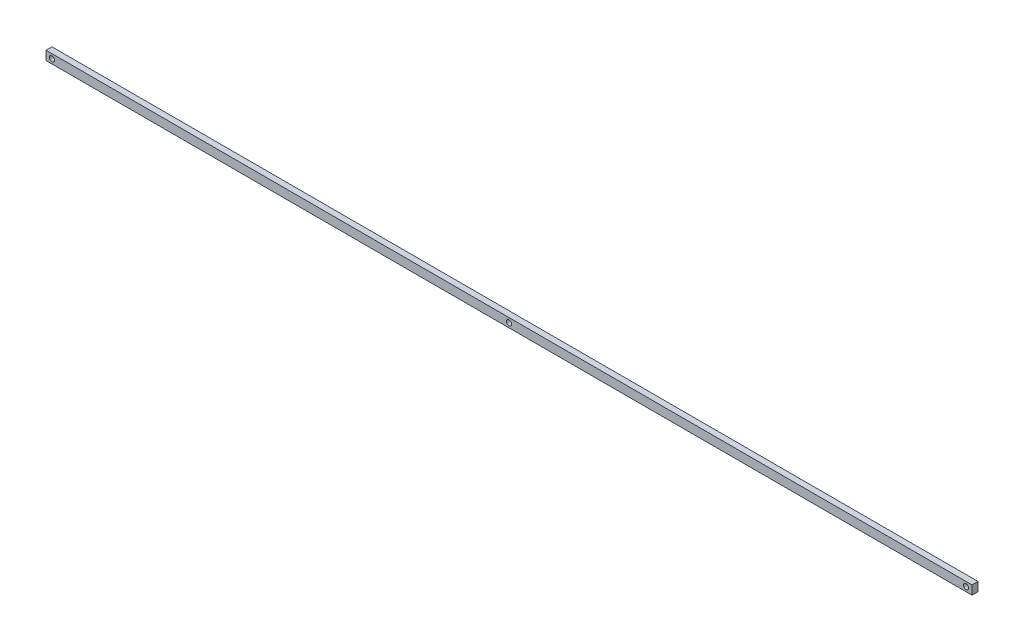
SolidWorks part; units mm, degrees
material "ASTM A36 Steel"
ref_plane "Front Plane" through (0, 0, 0) normal (0, 0, 1) x (1, 0, 0)
ref_plane "Top Plane" through (0, 0, 0) normal (0, 1, 0) x (1, 0, 0)
ref_plane "Right Plane" through (0, 0, 0) normal (1, 0, 0) x (0, 0, -1)
sketch "Sketch1" plane through (0, 0, 0) normal (0, 0, 1) x (1, 0, 0)
  line L0 (55, 0) -> (-55, 0) construction
  line L1 (0, 0) -> (1556, 0)
  line L2 (0, 0) -> (0, 15)
  line L3 (0, 15) -> (1556, 15)
  line L4 (1556, 0) -> (1556, 15)
  dimension "D1" = 1556
  dimension "D2" = 15
extrude "Boss-Extrude1" add sketch "Sketch1" along normal blind 10
sketch "Sketch2" plane through (0, 0, 10) normal (0, 0, 1) x (1, 0, 0)
  line L0 (0, 15) -> (0, 0) construction
  line L1 (0, 7.5) -> (-51.7723, 7.5) construction
  line L2 (778, 15) -> (778, 145.9267) construction
  line L3 (1556, 0) -> (1556, 15) construction
  line L4 (1556, 15) -> (0, 15) construction
  circle A0 centre (10, 7.5) radius 4.255
  circle A1 centre (1546, 7.5) radius 4.255
  circle A2 centre (778, 7.5) radius 4.255
  dimension "D1" = 8.51
  dimension "D2" = 10
  dimension "D3" = 10
extrude "Cut-Extrude1" cut sketch "Sketch2" against normal up to surface (10 mm away) up to face at (778, 7.5, 0)
